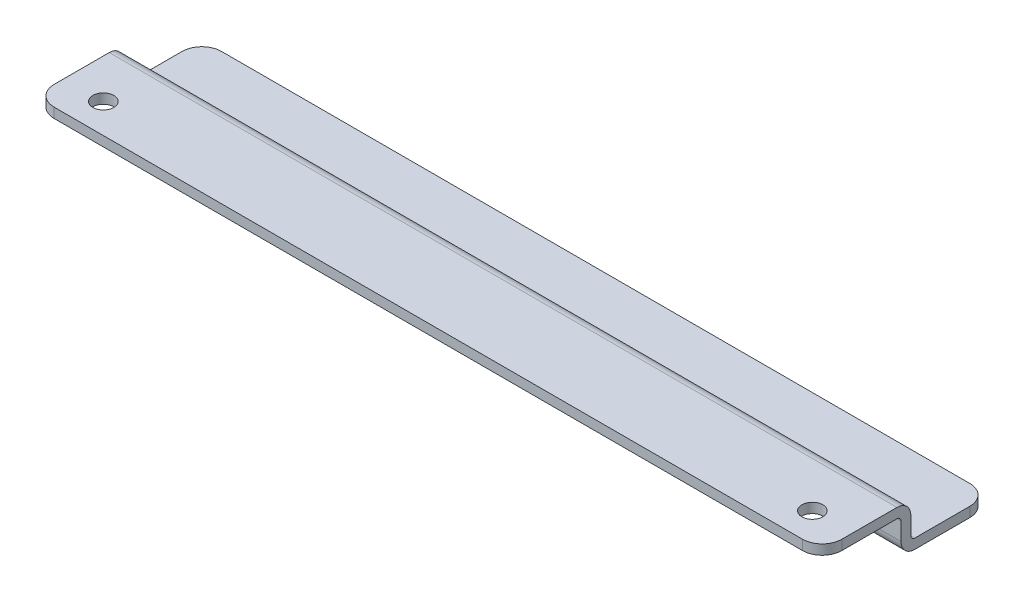
SolidWorks part; units mm, degrees
ref_plane "Front Plane" through (0, 0, 0) normal (0, 0, 1) x (1, 0, 0)
ref_plane "Top Plane" through (0, 0, 0) normal (0, 1, 0) x (1, 0, 0)
ref_plane "Right Plane" through (0, 0, 0) normal (1, 0, 0) x (0, 0, -1)
sketch "Sketch1" plane through (0, 0, 0) normal (1, 0, 0) x (0, 0, -1)
  line L0 (0, 0) -> (28.575, 0)
  line L1 (28.575, 0) -> (28.575, -11.43)
  line L2 (28.575, -11.43) -> (53.975, -11.43)
  line L3 (53.975, -11.43) -> (53.975, -14.605)
  line L4 (53.975, -14.605) -> (25.4, -14.605)
  line L5 (25.4, -14.605) -> (25.4, -3.175)
  line L6 (25.4, -3.175) -> (0, -3.175)
  line L7 (0, -3.175) -> (0, 0)
  dimension "D1" = 11.43
  dimension "D2" = 3.175
  dimension "D3" = 3.175
  dimension "D4" = 28.575
  dimension "D5" = 28.575
extrude "Boss-Extrude1" add sketch "Sketch1" along normal blind 254
fillet "Fillet1" radius 1.27 2 edges at (127, -11.43, -28.575) (127, -3.175, -25.4)
fillet "Fillet2" radius 4.445 2 edges at (127, -14.605, -25.4) (127, 0, -28.575)
hole_wizard "17/64 (0.26563) Diameter Hole1" positions "Sketch2" profile "Sketch3" hole size "17/64" standard "ANSI Inch" end condition up to next
sketch "Sketch2" plane through (0, 0, 0) normal (0, 1, 0) x (1, 0, 0)
  line L0 (254, 0) -> (0, 0) construction
  line L1 (254, 24.13) -> (254, 0) construction
  line L2 (0, 24.13) -> (0, 0) construction
  point P0 (241.3, 9.525)
  point P2 (12.7, 9.525)
  point P5 (0, 0)
  dimension "D1" = 9.525
  dimension "D2" = 12.7
  dimension "D3" = 12.7
sketch "Sketch3" plane through (241.3, 0, -9.525) normal (1, 0, 0) x (0, 0, 1)
  line L0 (0, 0) -> (0, 3.175)
  line L1 (0, 3.175) -> (3.3735, 3.175)
  line L2 (3.3735, 3.175) -> (3.3735, 0)
  line L5 (3.3735, 0) -> (0, 0)
  line L11 (0, -6.35) -> (0, 107.95) construction
  dimension "Thru Hole Dia." = 6.747
  dimension "Thru Hole Depth" = 3.175
fillet "Fillet3" radius 6.35 4 edges at (0, -13.0175, -53.975) (0, -1.5875, 0) (254, -13.0175, -53.975) (254, -1.5875, 0)
